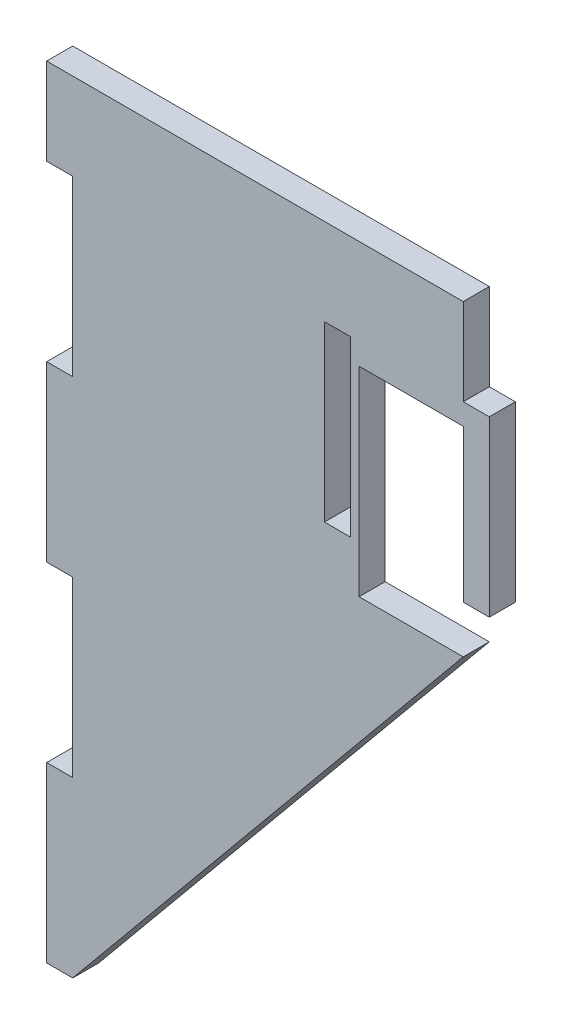
SolidWorks part; units mm, degrees
material "Acrilico TEC"
ref_plane "Front Plane" through (0, 0, 0) normal (0, 0, 1) x (1, 0, 0)
ref_plane "Top Plane" through (0, 0, 0) normal (0, 1, 0) x (1, 0, 0)
ref_plane "Right Plane" through (0, 0, 0) normal (1, 0, 0) x (0, 0, -1)
sketch "Sketch1" plane through (0, 0, 0) normal (0, 0, 1) x (1, 0, 0)
  line L0 (-3, 60) -> (-3, 40)
  line L1 (-3, 40) -> (0, 40)
  line L2 (0, 40) -> (0, 20)
  line L3 (0, 20) -> (-3, 20)
  line L4 (-3, 20) -> (-3, 0)
  line L5 (-3, 60) -> (0, 60)
  line L6 (0, 60) -> (0, 80)
  line L7 (0, 80) -> (-3, 80)
  line L8 (-3, 80) -> (-3, 90)
  line L9 (-3, 90) -> (15, 90)
  line L10 (15, 90) -> (15, 75) construction
  line L11 (-3, 0) -> (0, 0)
  line L12 (15, 90) -> (45, 90)
  line L13 (45, 54.5455) -> (33, 54.5455)
  line L14 (29, 80) -> (32, 80)
  line L15 (29, 60) -> (29, 80)
  line L16 (32, 60) -> (29, 60)
  line L17 (45, 90) -> (45, 80)
  line L18 (45, 80) -> (48, 80)
  line L19 (48, 80) -> (48, 60)
  line L20 (48, 60) -> (45, 60)
  line L21 (33, 54.5455) -> (33, 77.5455)
  line L22 (0, 0) -> (45, 54.5455)
  line L24 (33, 77.5455) -> (45, 77.5455)
  line L25 (32, 60) -> (32, 80)
  line L26 (45, 77.5455) -> (45, 60)
  dimension "D1" = 10
  dimension "D2" = 20
  dimension "D3" = 20
  dimension "D4" = 20
  dimension "D5" = 20
  dimension "D6" = 3
  dimension "D7" = 3
  dimension "D8" = 15
  dimension "D9" = 15
  dimension "D10" = 30
  dimension "D11" = 3
  dimension "D12" = 20
  dimension "D13" = 5.4545
  dimension "D14" = 20
  dimension "D15" = 3
  dimension "D16" = 3
  dimension "D17" = 14
  dimension "D18" = 10
  dimension "D20" = 23
extrude "Boss-Extrude1" add sketch "Sketch1" along normal blind 3
